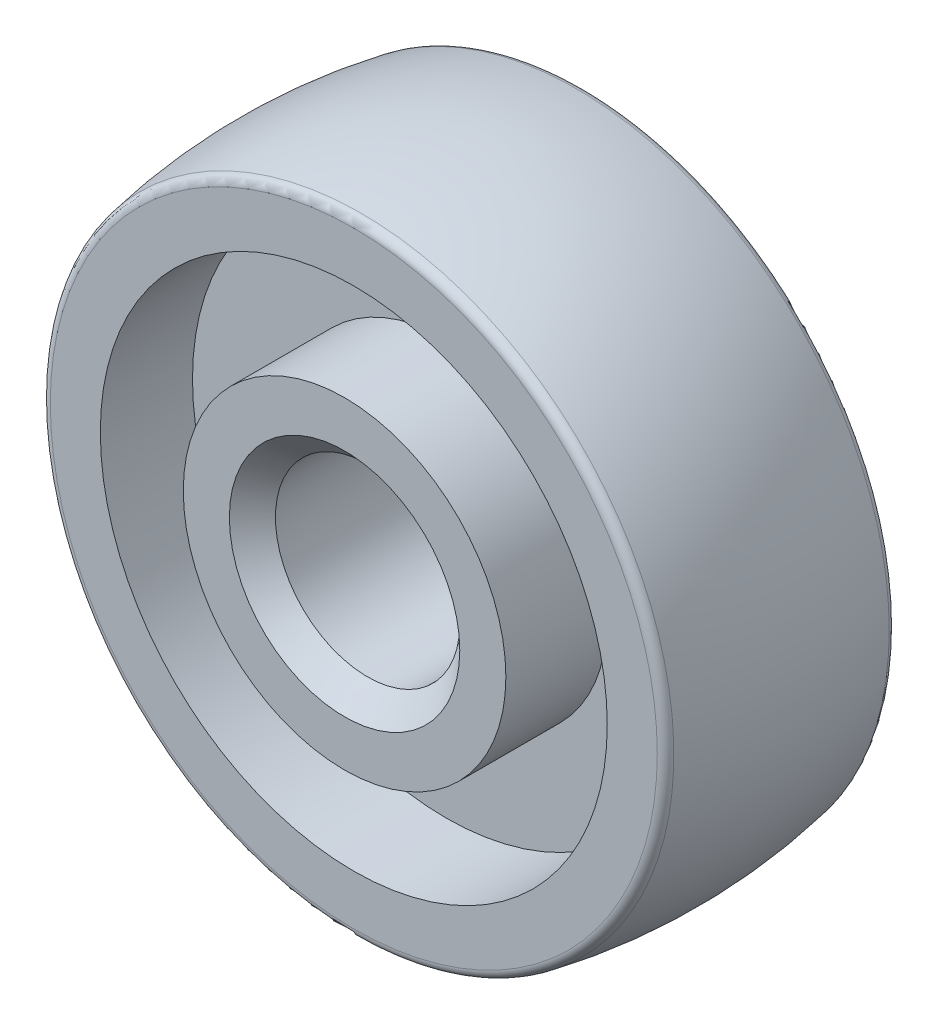
SolidWorks part; units mm, degrees
ref_plane "前视基准面" through (0, 0, 0) normal (0, 0, 1) x (1, 0, 0)
ref_plane "上视基准面" through (0, 0, 0) normal (0, 1, 0) x (1, 0, 0)
ref_plane "右视基准面" through (0, 0, 0) normal (1, 0, 0) x (0, 0, -1)
sketch "草图1" plane through (0, 0, 0) normal (1, 0, 0) x (0, 0, -1)
  line L1 (-3.6296, 0) -> (3.335, 0) construction
  line L2 (-2.5, 0) -> (-2.5, 6.75)
  line L3 (-2.5, 0) -> (2.5, 0)
  line L4 (2.5, 0) -> (2.5, 6.75)
  arc A0 (0, 7) -> (2.5, 6.75) centre (0, -5.625) cw
  arc A1 (0, 7) -> (-2.5, 6.75) centre (0, -5.625) ccw
revolve "旋转1" add sketch "草图1" angle 360 about L1
sketch "草图2" plane through (0, 0, 2.5) normal (0, 0, 1) x (1, 0, 0)
  circle A0 centre (0, 0) radius 3.5
extrude "凸台-拉伸1" add sketch "草图2" along normal blind 0.2 and the other way blind 5.2
sketch "草图3" plane through (0, 0, 2.7) normal (0, 0, 1) x (1, 0, 0)
  circle A0 centre (0, 0) radius 2
extrude "切除-拉伸1" cut sketch "草图3" against normal up to next
sketch "草图4" plane through (0, 0, 2.5) normal (0, 0, 1) x (1, 0, 0)
  circle A0 centre (0, 0) radius 5.5
  circle A1 centre (0, 0) radius 3.5
extrude "切除-拉伸2" cut sketch "草图4" against normal blind 2
sketch "草图5" plane through (0, 0, -2.5) normal (0, 0, -1) x (-1, 0, 0)
  circle A0 centre (0, 0) radius 5.5
  circle A1 centre (0, 0) radius 3.5
extrude "切除-拉伸3" cut sketch "草图5" against normal blind 2
fillet "圆角1" radius 0.2 2 edges at (6.75, 0, -2.5) (6.75, 0, 2.5)
chamfer "倒角1" distance 0.5 angle 45 2 edges at (2, 0, -2.7) (2, 0, 2.7)
